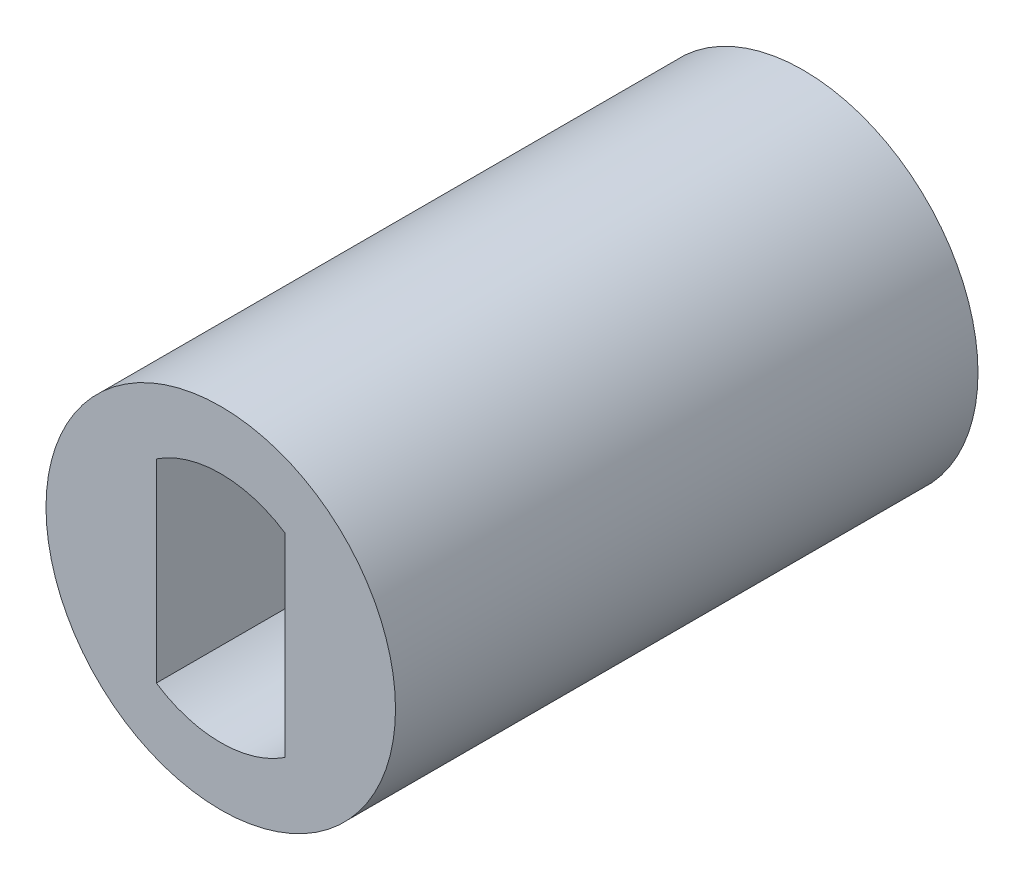
SolidWorks part; units mm, degrees
ref_plane "Front Plane" through (0, 0, 0) normal (0, 0, 1) x (1, 0, 0)
ref_plane "Top Plane" through (0, 0, 0) normal (0, 1, 0) x (1, 0, 0)
ref_plane "Right Plane" through (0, 0, 0) normal (1, 0, 0) x (0, 0, -1)
sketch "Sketch1" plane through (0, 0, 0) normal (0, 0, 1) x (1, 0, 0)
  line L4 (3.3166, 5) -> (-3.3166, 5)
  line L5 (3.3166, 5) -> (3.3166, -5)
  line L6 (3.3166, -5) -> (-3.3166, -5)
  line L7 (-3.3166, 5) -> (-3.3166, -5)
  circle A0 centre (0, 0) radius 6
  circle A2 centre (0, 0) radius 9
  dimension "D1" = 12
  dimension "D4" = 18
  dimension "D6" = 10
extrude "Boss-Extrude1" add sketch "Sketch1" along normal blind 30 contours A2 A0 | L7 A0 | L5 A0
